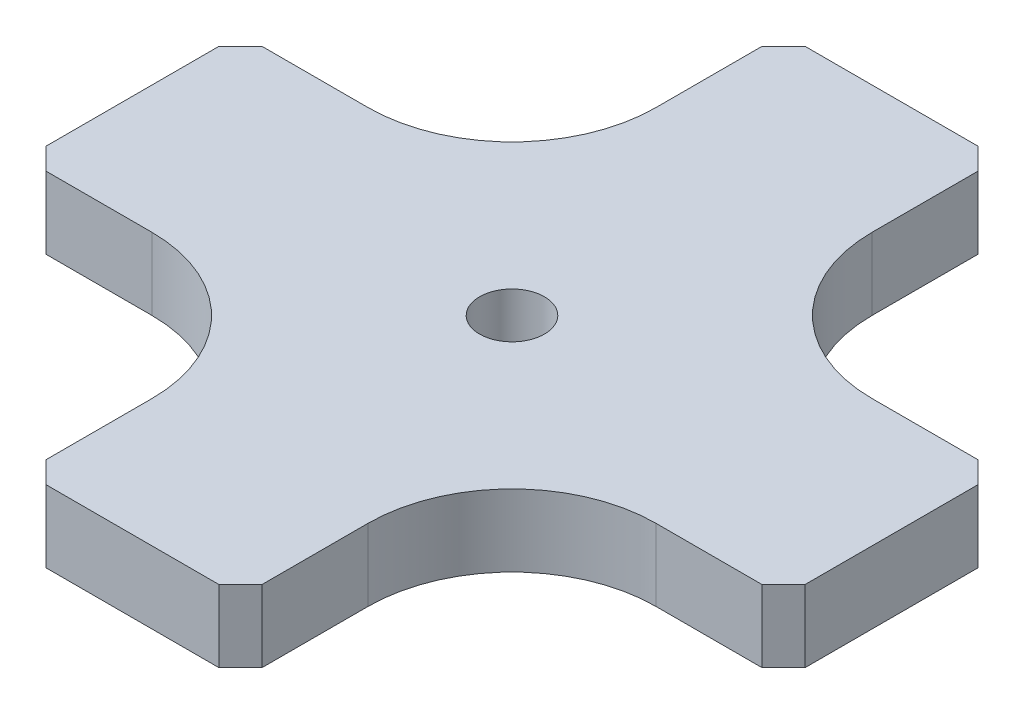
SolidWorks part; units mm, degrees
material "Thornel Mat VMA"
ref_plane "Front Plane" through (0, 0, 0) normal (0, 0, 1) x (1, 0, 0)
ref_plane "Top Plane" through (0, 0, 0) normal (0, 1, 0) x (1, 0, 0)
ref_plane "Right Plane" through (0, 0, 0) normal (1, 0, 0) x (0, 0, -1)
sketch "Sketch2" plane through (0, 0, 0) normal (0, 1, 0) x (1, 0, 0)
  line L0 (0, 0) -> (0, 26.35) construction
  line L1 (-7.5, 26.35) -> (7.5, 26.35)
  line L2 (7.5, 26.35) -> (7.5, 7.5)
  line L3 (0, 0) -> (7.5, 7.5) construction
  line L4 (26.35, 7.5) -> (7.5, 7.5)
  line L5 (26.35, -7.5) -> (26.35, 7.5)
  line L6 (-26.35, -7.5) -> (-26.35, 7.5)
  line L7 (-26.35, 7.5) -> (-7.5, 7.5)
  line L8 (-7.5, 26.35) -> (-7.5, 7.5)
  line L9 (0, 0) -> (-26.35, 0) construction
  line L10 (26.35, -7.5) -> (7.5, -7.5)
  line L11 (7.5, -26.35) -> (7.5, -7.5)
  line L12 (-7.5, -26.35) -> (7.5, -26.35)
  line L13 (-7.5, -26.35) -> (-7.5, -7.5)
  line L14 (-26.35, -7.5) -> (-7.5, -7.5)
  point P12 (26.35, 0)
  dimension "D1" = 7.5
  dimension "D3" = 26.35
extrude "Boss-Extrude1" add sketch "Sketch2" along normal mid plane 5
fillet "Fillet1" radius 10 4 edges at (-7.5, 0, -7.5) (7.5, 0, -7.5) (7.5, 0, 7.5) (-7.5, 0, 7.5)
chamfer "Chamfer1" distance 1.5 angle 45 8 edges at (-26.35, 0, 7.5) (-26.35, 0, -7.5) (-7.5, 0, -26.35) (7.5, 0, -26.35) (26.35, 0, -7.5) (26.35, 0, 7.5) (7.5, 0, 26.35) (-7.5, 0, 26.35)
hole_wizard "M4 Clearance Hole1" positions "Sketch3" profile "Sketch4" hole size "M4" standard "ANSI Metric"
sketch "Sketch3" plane through (0, 2.5, 0) normal (0, 1, 0) x (1, 0, 0)
  point P0 (0, 0)
sketch "Sketch4" plane through (0, 2.5, 0) normal (1, 0, 0) x (0, 0, 1)
  line L0 (0, 0) -> (0, 6.5519)
  line L1 (0, 6.5519) -> (2.25, 5.2)
  line L2 (2.25, 5.2) -> (2.25, 0)
  line L5 (2.25, 0) -> (0, 0)
  line L10 (0, 6.5519) -> (-2.25, 5.2) construction
  line L11 (0, -6.35) -> (0, 107.95) construction
  dimension "Hole Dia." = 4.5
  dimension "Hole Depth" = 5.2
  dimension "Drill Angle" = 118
